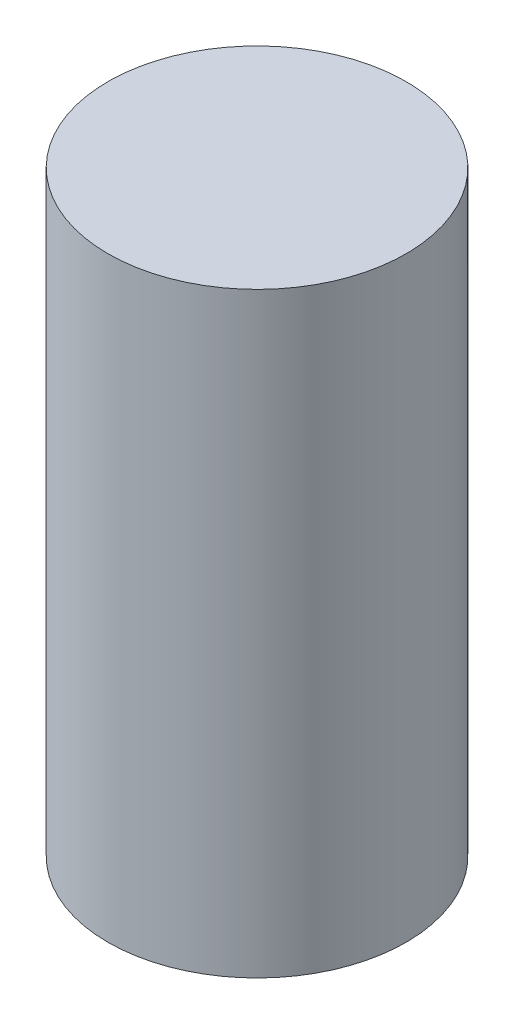
SolidWorks part; units mm, degrees
ref_plane "前视基准面" through (0, 0, 0) normal (0, 0, 1) x (1, 0, 0)
ref_plane "上视基准面" through (0, 0, 0) normal (0, 1, 0) x (1, 0, 0)
ref_plane "右视基准面" through (0, 0, 0) normal (1, 0, 0) x (0, 0, -1)
other "Configuration Table"
sketch "草图1" plane through (0, 0, 0) normal (0, 1, 0) x (1, 0, 0)
  circle A0 centre (0, 0) radius 7.5
  dimension "D1" = 15
extrude "凸台-拉伸1" add sketch "草图1" along normal blind 30
sketch "草图2" plane through (0, 0, 0) normal (0, -1, 0) x (1, 0, 0)
  circle A0 centre (0, 0) radius 2.25
  dimension "D1" = 4.5
extrude "切除-拉伸1" cut sketch "草图2" against normal blind 20
